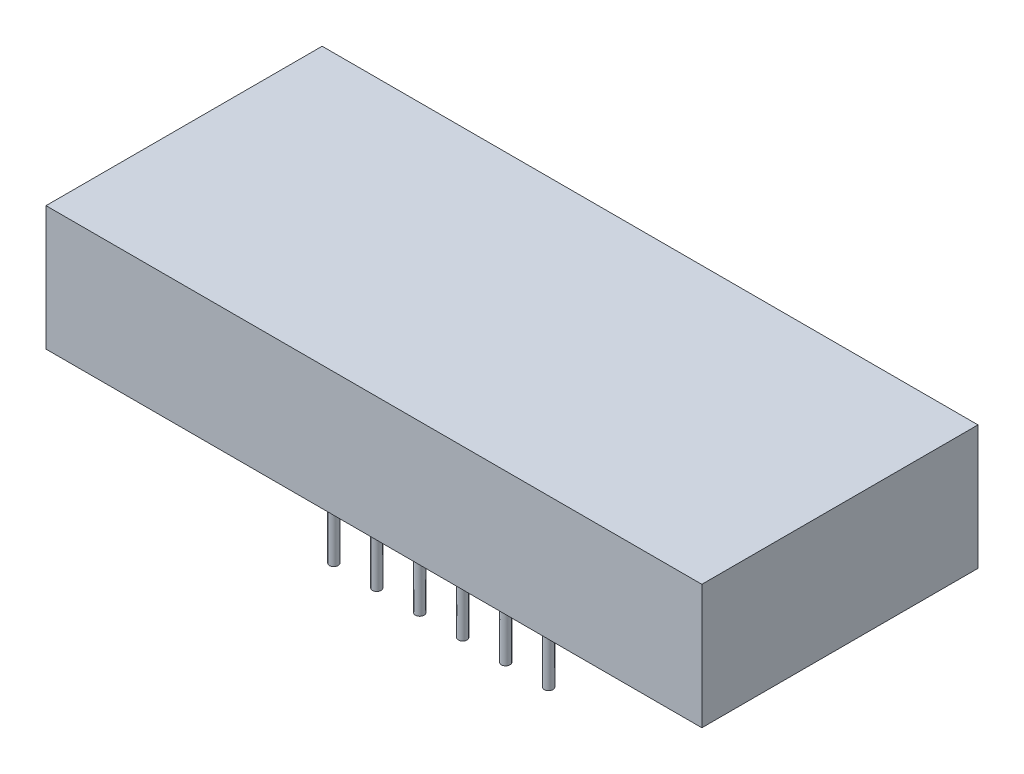
SolidWorks part; units mm, degrees
ref_plane "前视基准面" through (0, 0, 0) normal (0, 0, 1) x (1, 0, 0)
ref_plane "上视基准面" through (0, 0, 0) normal (0, 1, 0) x (1, 0, 0)
ref_plane "右视基准面" through (0, 0, 0) normal (1, 0, 0) x (0, 0, -1)
sketch "草图1" plane through (0, 0, 0) normal (0, 1, 0) x (1, 0, 0)
  line L0 (-29.3463, 0) -> (31.8739, 0) construction
  line L1 (-19, 8) -> (19, 8)
  line L2 (-19, 8) -> (-19, -8)
  line L3 (-19, -8) -> (19, -8)
  line L4 (19, 8) -> (19, -8)
  line L5 (0, 30.3794) -> (0, -29.5342) construction
  dimension "D1" = 38
  dimension "D2" = 16
extrude "拉伸1" add sketch "草图1" along normal blind 7.2
sketch "草图2" plane through (0, 0, 0) normal (0, -1, 0) x (1, 0, 0)
  line L0 (22.7617, 0) -> (-24.809, 0) construction
  line L1 (0, 10.3572) -> (0, -11.9228) construction
  line L2 (5.6198, 4.1) -> (-6.2174, 4.1) construction
  line L3 (5.6198, -4.1) -> (-6.2174, -4.1) construction
  circle A0 centre (6.2247, 4.1) radius 0.25
  circle A1 centre (3.7348, 4.1) radius 0.25
  circle A2 centre (1.2449, 4.1) radius 0.25
  circle A3 centre (-1.2449, 4.1) radius 0.25
  circle A4 centre (-3.7348, 4.1) radius 0.25
  circle A5 centre (-6.2247, 4.1) radius 0.25
  circle A6 centre (-6.2247, -4.1) radius 0.25
  circle A7 centre (-3.7348, -4.1) radius 0.25
  circle A8 centre (-1.2449, -4.1) radius 0.25
  circle A9 centre (1.2449, -4.1) radius 0.25
  circle A10 centre (3.7348, -4.1) radius 0.25
  circle A11 centre (6.2247, -4.1) radius 0.25
  dimension "D1" = 0.5
  dimension "D2" = 8.2
extrude "拉伸2" add sketch "草图2" along normal blind 6.3
